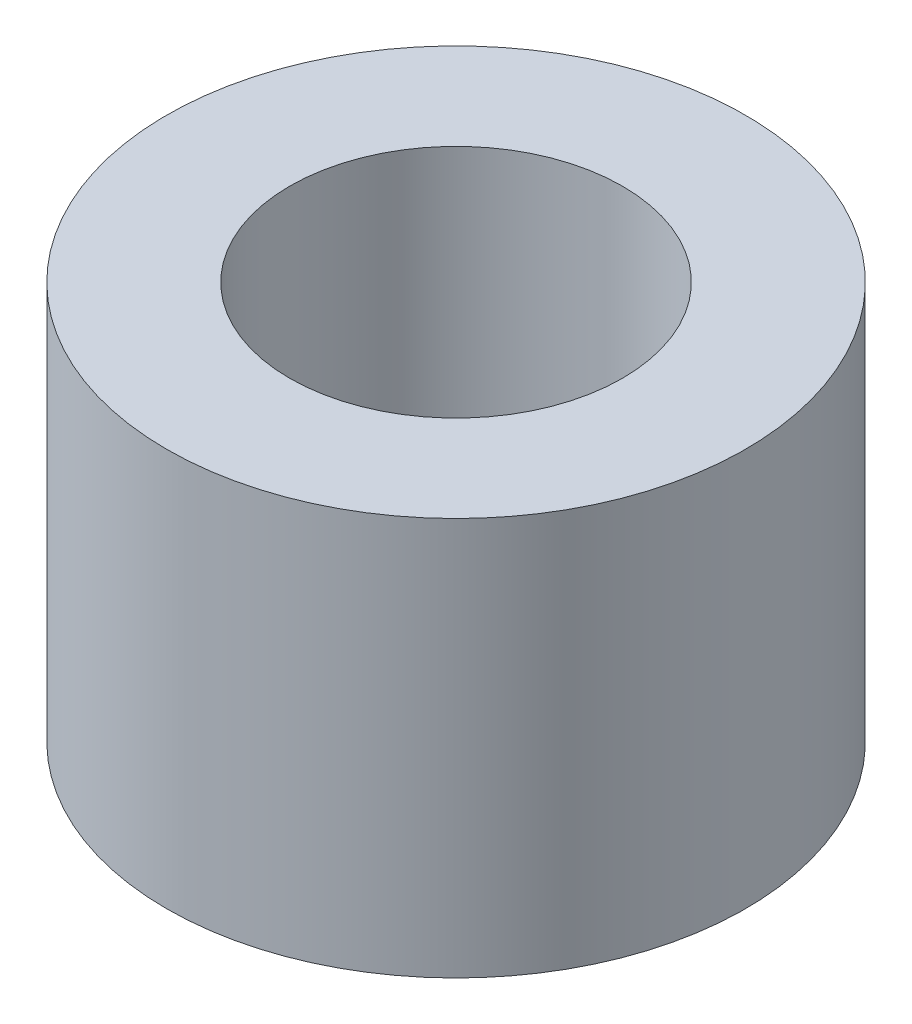
SolidWorks part; units mm, degrees
ref_plane "Front Plane" through (0, 0, 0) normal (0, 0, 1) x (1, 0, 0)
ref_plane "Top Plane" through (0, 0, 0) normal (0, 1, 0) x (1, 0, 0)
ref_plane "Right Plane" through (0, 0, 0) normal (1, 0, 0) x (0, 0, -1)
sketch "Sketch1" plane through (0, 0, 0) normal (0, 1, 0) x (1, 0, 0)
  circle A0 centre (-42.7098, 13.2457) radius 4
  circle A1 centre (-42.7098, 13.2457) radius 2.3
extrude "Boss-Extrude1" add sketch "Sketch1" along normal blind 5.5
